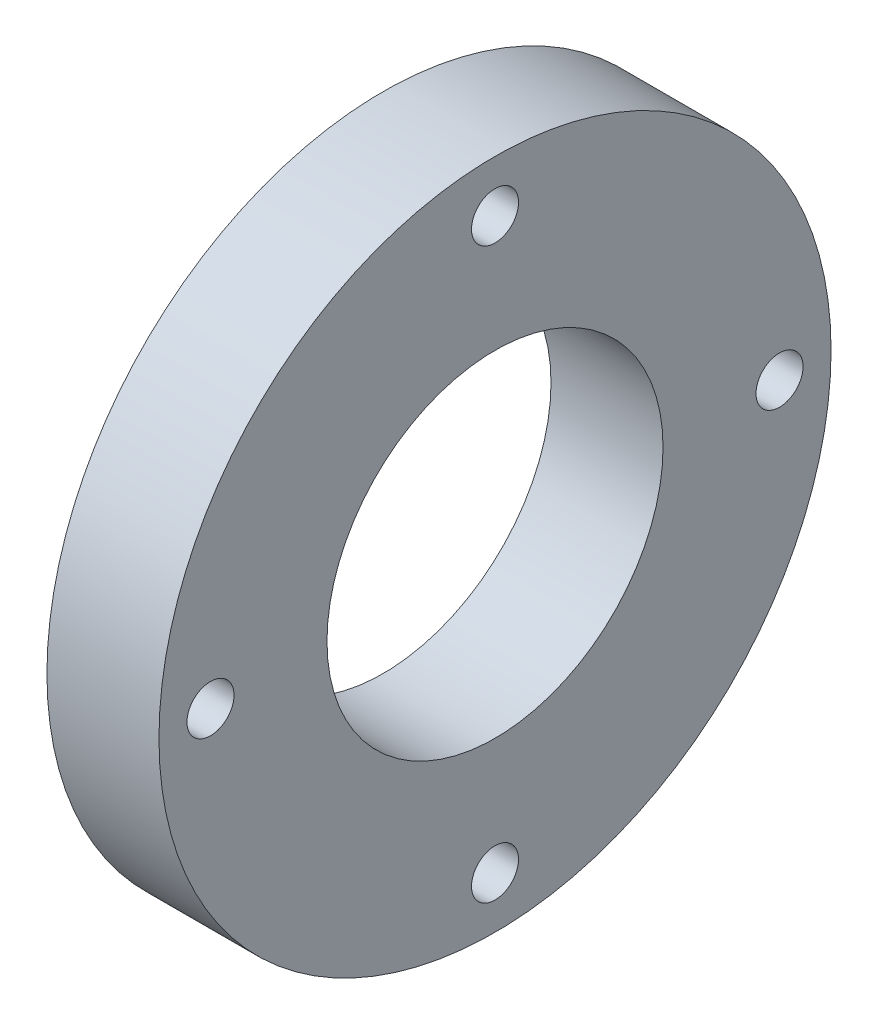
SolidWorks part; units mm, degrees
material "AISI 304"
ref_plane "Front Plane" through (0, 0, 0) normal (0, 0, 1) x (1, 0, 0)
ref_plane "Top Plane" through (0, 0, 0) normal (0, 1, 0) x (1, 0, 0)
ref_plane "Right Plane" through (0, 0, 0) normal (1, 0, 0) x (0, 0, -1)
sketch "Sketch1" plane through (0, 0, 0) normal (0, 0, 1) x (1, 0, 0)
  line L0 (21, 15) -> (21, 0)
  line L1 (21, 0) -> (26, 0)
  line L2 (26, 0) -> (26, 15)
  line L3 (26, 15) -> (21, 15)
  line L4 (21, 0) -> (26, 0) construction
revolve "Revolve1" add sketch "Sketch1" angle 360 about L4
hole_wizard "Ø15.0 (15) Diameter Hole1" positions "Sketch3" profile "Sketch2" hole size "Ø15.0" standard "ANSI Metric"
sketch "Sketch3" plane through (21, 0, 0) normal (-1, 0, 0) x (0, 0, 1)
  point P0 (0, 0)
sketch "Sketch2" plane through (21, 0, 0) normal (0, 1, 0) x (0, 0, 1)
  line L0 (0, 0) -> (0, 5)
  line L1 (0, 5) -> (7.5, 5)
  line L2 (7.5, 5) -> (7.5, 0)
  line L5 (7.5, 0) -> (0, 0)
  line L11 (0, -6.35) -> (0, 107.95) construction
  dimension "Thru Hole Dia." = 15
  dimension "Thru Hole Depth" = 5
hole_wizard "Ø2.1 (2.1) Diameter Hole1" positions "Sketch5" profile "Sketch4" hole size "Ø2.1" standard "ANSI Metric"
sketch "Sketch5" plane through (26, 0, 0) normal (1, 0, 0) x (0, 0, -1)
  point P0 (-12.7, 0)
  point P1 (12.7, 0)
  point P2 (0, -12.7)
  point P3 (0, 12.7)
sketch "Sketch4" plane through (26, 0, 12.7) normal (0, 1, 0) x (0, 0, -1)
  line L0 (0, 0) -> (0, 2.5)
  line L1 (0, 2.5) -> (1.05, 2.5)
  line L2 (1.05, 2.5) -> (1.05, 0)
  line L5 (1.05, 0) -> (0, 0)
  line L10 (0, 2.5) -> (-1.05, 2.5) construction
  line L11 (0, -6.35) -> (0, 107.95) construction
  dimension "Hole Dia." = 2.1
  dimension "Hole Depth" = 2.5
  dimension "Drill Angle" = 180
